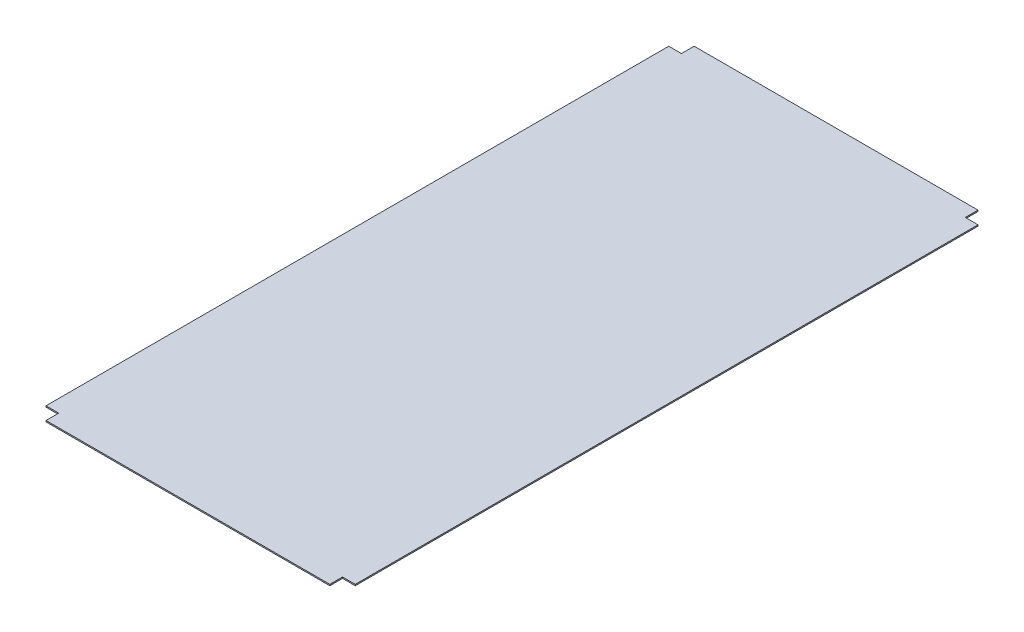
SolidWorks part; units mm, degrees
ref_plane "Alzado" through (0, 0, 0) normal (0, 0, 1) x (1, 0, 0)
ref_plane "Planta" through (0, 0, 0) normal (0, 1, 0) x (1, 0, 0)
ref_plane "Vista lateral" through (0, 0, 0) normal (1, 0, 0) x (0, 0, -1)
sketch "Croquis1" plane through (0, 0, 0) normal (0, 1, 0) x (1, 0, 0)
  line L1 (365, -765) -> (-365, -765)
  line L2 (365, -765) -> (365, 765)
  line L3 (365, 765) -> (-365, 765)
  line L4 (-365, -765) -> (-365, 765)
  line L5 (365, -765) -> (-365, 765) construction
  line L6 (365, 765) -> (-365, -765) construction
  point P0 (0, 0)
  dimension "D1" = 1530
  dimension "D2" = 730
extrude "Saliente-Extruir1" add sketch "Croquis1" along normal blind 3 contours L4 L3 L2 L1
sketch "Croquis2" plane through (0, 3, 0) normal (0, 1, 0) x (1, 0, 0)
  line L1 (-365, 765) -> (-335, 765)
  line L2 (-365, 765) -> (-365, 735)
  line L3 (-365, 735) -> (-335, 735)
  line L4 (-335, 765) -> (-335, 735)
  line L5 (365, 765) -> (335, 765)
  line L6 (365, 765) -> (365, 735)
  line L7 (365, 735) -> (335, 735)
  line L8 (335, 765) -> (335, 735)
  line L9 (365, -765) -> (335, -765)
  line L10 (365, -765) -> (365, -735)
  line L11 (365, -735) -> (335, -735)
  line L12 (335, -765) -> (335, -735)
  line L13 (-365, -765) -> (-335, -765)
  line L14 (-365, -765) -> (-365, -735)
  line L15 (-365, -735) -> (-335, -735)
  line L16 (-335, -765) -> (-335, -735)
  dimension "D1" = 30
extrude "Cortar-Extruir1" cut sketch "Croquis2" against normal through all
